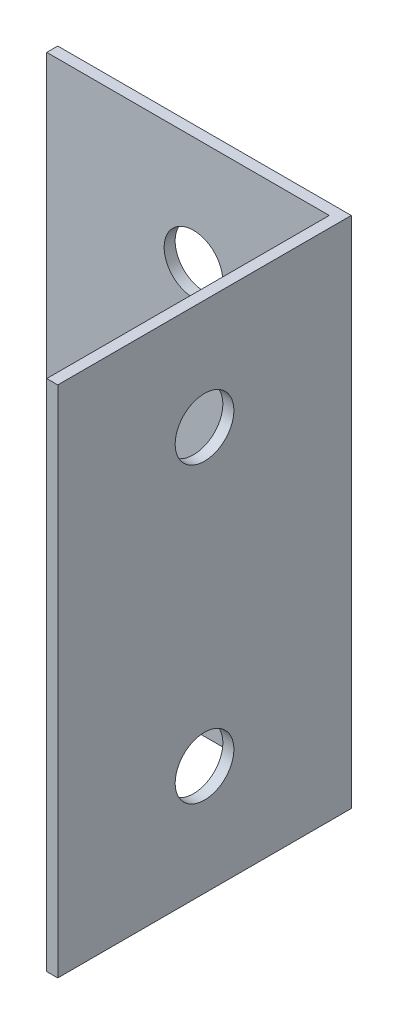
SolidWorks part; units mm, degrees
ref_plane "Płaszczyzna przednia" through (0, 0, 0) normal (0, 0, 1) x (1, 0, 0)
ref_plane "Płaszczyzna górna" through (0, 0, 0) normal (0, 1, 0) x (1, 0, 0)
ref_plane "Płaszczyzna prawa" through (0, 0, 0) normal (1, 0, 0) x (0, 0, -1)
sketch "Szkic1" plane through (0, 0, 0) normal (0, 0, 1) x (1, 0, 0)
  line L1 (20, -35) -> (-20, -35)
  line L2 (20, -35) -> (20, 35)
  line L3 (20, 35) -> (-20, 35)
  line L4 (-20, -35) -> (-20, 35)
  line L5 (20, -35) -> (-20, 35) construction
  line L6 (20, 35) -> (-20, -35) construction
  point P0 (0, 0)
  dimension "D1" = 40
  dimension "D2" = 70
extrude "Dodanie-wyciągnięcie1" add sketch "Szkic1" along normal blind 40
sketch "Szkic2" plane through (0, 35, 0) normal (0, 1, 0) x (1, 0, 0)
  line L0 (20, 0) -> (-20, 0) construction
  line L1 (-20, -40) -> (18.5, -40)
  line L2 (-20, -40) -> (-20, -1.5)
  line L3 (-20, -1.5) -> (18.5, -1.5)
  line L4 (18.5, -40) -> (18.5, -1.5)
  line L5 (20, -40) -> (20, 0) construction
  dimension "D1" = 1.5
  dimension "D2" = 1.5
extrude "Wytnij-wyciągnięcie1" cut sketch "Szkic2" against normal blind 80
sketch "Szkic3" plane through (18.5, 0, 0) normal (-1, 0, 0) x (0, 0, 1)
  line L2 (-10.4856, 0) -> (43.7114, 0) construction
  line L4 (40, -35) -> (40, 35) construction
  circle A0 centre (20, 20) radius 4
  circle A1 centre (20, -20) radius 4
  dimension "D1" = 8
  dimension "D2" = 20
  dimension "D3" = 40
extrude "Wytnij-wyciągnięcie2" cut sketch "Szkic3" against normal blind 80
sketch "Szkic11" plane through (0, 0, 1.5) normal (0, 0, 1) x (1, 0, 0)
  line L0 (-24.8786, 0) -> (39.8788, 0) construction
  circle A0 centre (0, 20) radius 4
  circle A1 centre (0, -20) radius 4
  point P5 (0, 0)
  dimension "D2" = 8
  dimension "D1" = 40
extrude "Wytnij-wyciągnięcie3" cut sketch "Szkic11" against normal blind 40
